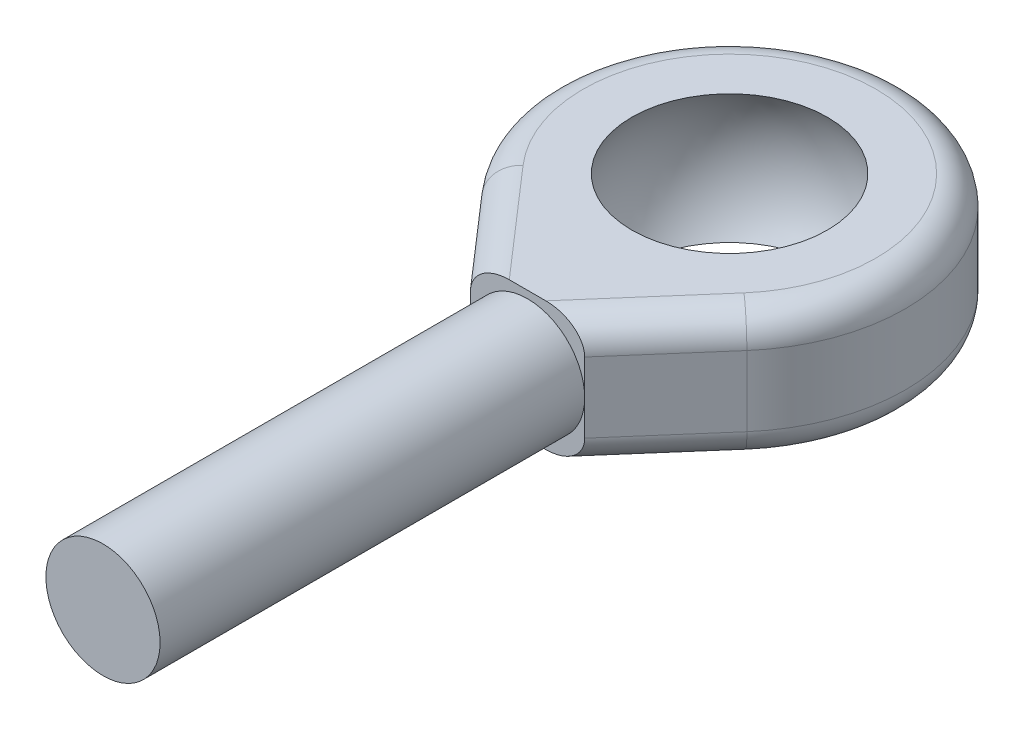
SolidWorks part; units mm, degrees
ref_plane "Front Plane" through (0, 0, 0) normal (0, 0, 1) x (1, 0, 0)
ref_plane "Top Plane" through (0, 0, 0) normal (0, 1, 0) x (1, 0, 0)
ref_plane "Right Plane" through (0, 0, 0) normal (1, 0, 0) x (0, 0, -1)
sketch "Sketch1" plane through (0, 0, 0) normal (0, 1, 0) x (1, 0, 0)
  circle A1 centre (0, 0) radius 12
  dimension "D1" = 24
extrude "Boss-Extrude1" add sketch "Sketch1" along normal blind 8.8
ref_plane "Plane1" through (0, 4.4, 0) normal (0, 1, 0) x (1, 0, 0)
sketch "Sketch2" plane through (0, 4.4, 0) normal (0, 1, 0) x (1, 0, 0)
  line L0 (-8, 0) -> (8, 0)
  arc A0 (8, 0) -> (-8, 0) centre (0, 0) ccw
  dimension "D1" = 16
revolve "Cut-Revolve1" cut sketch "Sketch2" angle 360 about L0
sketch "Sketch3" plane through (0, 8.8, 0) normal (0, 1, 0) x (1, 0, 0)
  line L0 (-3.9, -42.8) -> (3.9, -42.8)
  line L1 (0, -12) -> (0, -42.8)
  line L3 (-3.9, -11.3486) -> (-3.9, -42.8)
  line L6 (3.9, -11.3486) -> (3.9, -42.8)
  circle A1 centre (0, 0) radius 12 construction
  arc A2 (-3.9, -11.3486) -> (3.9, -11.3486) centre (0, 0) ccw
  circle M4 centre (0, 0) radius 12
extrude "Boss-Extrude2" add sketch "Sketch3" against normal blind 8.8 contours L6 L1 L0 M4 | L3 L0 L1 M4
sketch "Sketch4" plane through (0, 8.8, 0) normal (0, 1, 0) x (1, 0, 0)
  line L0 (0, -42.8) -> (0, -13.8)
  line L1 (-3.9, -42.8) -> (3.9, -42.8) construction
  line L2 (0, -13.8) -> (3.9, -13.8)
  line L3 (3.9, -11.3486) -> (3.9, -42.8) construction
  line L4 (3.9, -13.8) -> (-3.9, -13.8)
  line L5 (-3.9, -11.3486) -> (-3.9, -42.8) construction
  line L6 (9.0535, -7.8762) -> (3.9, -13.8)
  line L7 (-9.0535, -7.8762) -> (-3.9, -13.8)
  line L11 (-3.9, -11.3486) -> (-3.9, -42.8)
  line L12 (-3.9, -42.8) -> (3.9, -42.8)
  line L13 (3.9, -42.8) -> (3.9, -11.3486)
  line L14 (-3.9, -11.3486) -> (-3.9, -13.8)
  line L15 (-3.9, -42.8) -> (3.9, -42.8)
  line L16 (3.9, -13.8) -> (3.9, -11.3486)
  arc A0 (3.9, -11.3486) -> (-3.9, -11.3486) centre (0, 0) ccw construction
  arc A1 (-9.0535, -7.8762) -> (-3.9, -11.3486) centre (0, 0) ccw
  arc A2 (3.9, -11.3486) -> (-3.9, -11.3486) centre (0, 0) ccw
  arc A3 (3.9, -11.3486) -> (9.0535, -7.8762) centre (0, 0) ccw
  arc M7 (3.9, -11.3486) -> (-3.9, -11.3486) centre (0, 0) ccw
  line M8 (-3.9, -11.3486) -> (-3.9, -42.8)
  line M10 (3.9, -42.8) -> (3.9, -11.3486)
  dimension "D1" = 29
  dimension "D2" = 0
extrude "Boss-Extrude3" add sketch "Sketch4" along normal blind 8.8 separate body contours L7 M7 M8 | L6 M7 M10
sketch "Sketch5" plane through (0, 8.8, 0) normal (0, -1, 0) x (1, 0, 0)
  line L2 (-3.9, 11.3486) -> (-3.9, 13.8)
  line L3 (-3.9, 13.8) -> (-9.0535, 7.8762)
  line L4 (-3.9, 11.3486) -> (-3.9, 13.8)
  line L5 (-3.9, 13.8) -> (-9.0535, 7.8762)
  line L6 (9.0535, 7.8762) -> (3.9, 13.8)
  line L7 (3.9, 13.8) -> (3.9, 11.3486)
  line L8 (9.0535, 7.8762) -> (3.9, 13.8)
  line L9 (3.9, 13.8) -> (3.9, 11.3486)
  arc A1 (-3.9, 11.3486) -> (-9.0535, 7.8762) centre (0, 0) ccw
  arc A2 (-3.9, 11.3486) -> (-9.0535, 7.8762) centre (0, 0) ccw
  arc A3 (9.0535, 7.8762) -> (3.9, 11.3486) centre (0, 0) ccw
  arc A4 (9.0535, 7.8762) -> (3.9, 11.3486) centre (0, 0) ccw
  dimension "D1" = 0
  dimension "D2" = 0
extrude "Boss-Extrude4" add sketch "Sketch5" along normal blind 8.8
sketch "Sketch6" plane through (0, 17.6, 0) normal (0, 1, 0) x (1, 0, 0)
  line L2 (-9.0535, -7.8762) -> (-3.9, -13.8)
  line L3 (-3.9, -13.8) -> (-3.9, -11.3486)
  line L4 (-9.0535, -7.8762) -> (-3.9, -13.8)
  line L5 (-3.9, -13.8) -> (-3.9, -11.3486)
  line L6 (3.9, -13.8) -> (9.0535, -7.8762)
  line L7 (3.9, -11.3486) -> (3.9, -13.8)
  line L8 (3.9, -13.8) -> (9.0535, -7.8762)
  line L9 (3.9, -11.3486) -> (3.9, -13.8)
  arc A1 (-9.0535, -7.8762) -> (-3.9, -11.3486) centre (0, 0) ccw
  arc A2 (-9.0535, -7.8762) -> (-3.9, -11.3486) centre (0, 0) ccw
  arc A3 (3.9, -11.3486) -> (9.0535, -7.8762) centre (0, 0) ccw
  arc A4 (3.9, -11.3486) -> (9.0535, -7.8762) centre (0, 0) ccw
  dimension "D1" = 0
  dimension "D2" = 0
extrude "Cut-Extrude3" cut sketch "Sketch6" against normal blind 8.8
sketch "Sketch7" plane through (0, 0, 42.8) normal (0, 0, 1) x (1, 0, 0)
  line L0 (0, 8.8) -> (0, 0)
  line L1 (-3.9, 8.8) -> (3.9, 8.8) construction
  line L6 (3.9, 8.8) -> (-3.9, 8.8)
  line L7 (-3.9, 8.8) -> (-3.9, 0)
  line L8 (-3.9, 0) -> (3.9, 0)
  line L9 (3.9, 0) -> (3.9, 8.8)
  line L10 (3.9, 8.8) -> (-3.9, 8.8)
  line L11 (-3.9, 8.8) -> (-3.9, 0)
  line L12 (-3.9, 0) -> (3.9, 0)
  line L13 (3.9, 0) -> (3.9, 8.8)
  circle A0 centre (0, 4.4) radius 3.9
  line M5 (3.9, 8.8) -> (-3.9, 8.8)
  line M6 (-3.9, 8.8) -> (-3.9, 0)
  line M7 (-3.9, 0) -> (3.9, 0)
  line M8 (3.9, 0) -> (3.9, 8.8)
  dimension "D1" = 0
extrude "Cut-Extrude4" cut sketch "Sketch7" against normal blind 29 contours A0 L13 L0 M5 | A0 L0 M7 M8 | A0 L0 M5 M6 | A0 L11 L0 M7
fillet "Fillet1" radius 2 6 edges at (6.4767, 0, 10.8381) (0, 0, -12) (6.4767, 8.8, 10.8381) (0, 8.8, -12) (-6.4767, 0, 10.8381) (-6.4767, 8.8, 10.8381)
